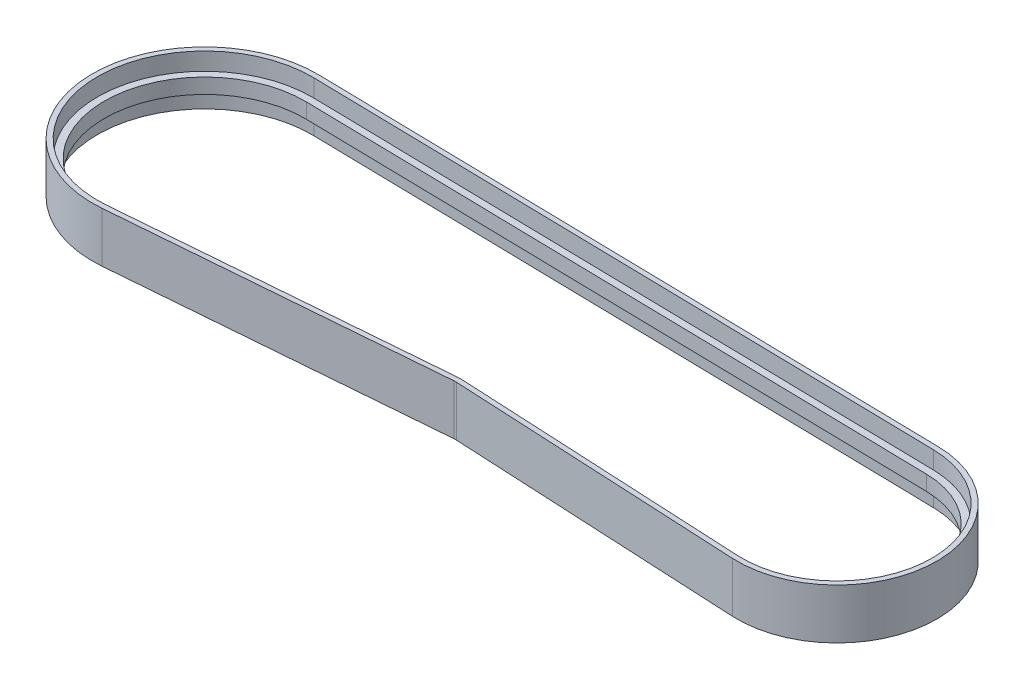
SolidWorks part; units mm, degrees
other "Markup1"
sketch "Sketch2" plane through (-23.4, 0, -23.4) normal (-0.231, -0.9167, -0.326) x (-0.972, 0.232, 0.0366)
sketch "Sketch3" plane through (-22.35, 0, -22.35) normal (-0.231, -0.9167, -0.326) x (-0.972, 0.232, 0.0366)
sketch "Sketch4" plane through (-22.35, 0, -22.35) normal (-0.231, -0.9167, -0.326) x (-0.972, 0.232, 0.0366)
sketch "Sketch5" plane through (-22.35, 0, -22.35) normal (-0.231, -0.9167, -0.326) x (-0.972, 0.232, 0.0366)
sketch "Sketch6" plane through (-22.35, 0, -22.35) normal (-0.231, -0.9167, -0.326) x (-0.972, 0.232, 0.0366)
sketch "Sketch9" plane through (-22.35, -5, -22.35) normal (-0.231, -0.9167, -0.326) x (-0.972, 0.232, 0.0366)
material "BUTYL"
ref_plane "Front Plane" through (0, 0, 0) normal (0, 0, 1) x (1, 0, 0)
ref_plane "Top Plane" through (0, 0, 0) normal (0, 1, 0) x (1, 0, 0)
ref_plane "Right Plane" through (0, 0, 0) normal (1, 0, 0) x (0, 0, -1)
sketch "Sketch1" plane through (0, 0, 0) normal (0, 1, 0) x (1, 0, 0)
  line L0 (0, 0) -> (126, 0) construction
  line L1 (0.4151, 21.346) -> (126.3675, 18.8964)
  line L2 (0.4346, 22.3458) -> (126.3869, 19.8962)
  line L5 (0.423, -21.3458) -> (125.0528, -18.8763) construction
  line L6 (0.4428, -22.3456) -> (125.0381, -19.8767) construction
  line L7 (125.0528, -18.8763) -> (67.15, -15.9709)
  line L8 (125.0381, -19.8767) -> (67.1167, -16.9704)
  line L9 (1.7388, -21.2791) -> (66.5748, -15.981)
  line L10 (1.8203, -22.2758) -> (66.6563, -16.9776)
  line L11 (0, 0) -> (66.9413, -20.466) construction
  arc A0 (0.4151, 21.346) -> (1.7388, -21.2791) centre (0, 0) ccw
  arc A1 (125.0528, -18.8763) -> (126.3675, 18.8964) centre (126, 0) ccw
  arc A2 (125.0381, -19.8767) -> (126.3869, 19.8962) centre (126, 0) ccw
  arc A3 (0.4346, 22.3458) -> (1.8203, -22.2758) centre (0, 0) ccw
  circle A4 centre (0, 0) radius 70 construction
  circle A5 centre (66.9413, -20.466) radius 1.25 construction
  arc A6 (67.1167, -16.9704) -> (66.6563, -16.9776) centre (66.9413, -20.466) ccw
  arc A8 (67.15, -15.9709) -> (66.5748, -15.981) centre (66.9413, -20.466) ccw
  arc A9 (0.4346, 22.3458) -> (0.4428, -22.3456) centre (0, 0) ccw construction
  arc A10 (0.4151, 21.346) -> (0.423, -21.3458) centre (0, 0) ccw construction
  point P17 (0, 0)
  point P22 (67.1167, -15.981)
  dimension "D1" = 42.7
  dimension "D3" = 37.8
  dimension "D5" = 140
  dimension "D6" = 7
  dimension "D7" = 2.5
  dimension "D9" = 1
  dimension "D2" = 126
  dimension "D8" = 17
  dimension "D4" = 1
extrude "Boss-Extrude1" add sketch "Sketch1" along normal mid plane 10
sketch "Sketch8" plane through (0, 0, 0) normal (0, 1, 0) x (1, 0, 0)
  line L15 (67.2177, -14.5725) -> (125.123, -17.478)
  line L16 (126.3403, 17.4967) -> (0.3879, 19.9462)
  line L17 (1.6248, -19.8837) -> (66.4608, -14.5856)
  line L18 (67.2177, -14.5725) -> (125.123, -17.478)
  line L19 (126.3403, 17.4967) -> (0.3879, 19.9462)
  line L20 (1.6248, -19.8837) -> (66.4608, -14.5856)
  line L32 (67.1404, -16.1706) -> (125.0428, -19.076)
  line L33 (126.3714, 19.0964) -> (0.419, 21.5459)
  line L34 (1.7551, -21.4784) -> (66.5911, -16.1803)
  line L35 (67.1404, -16.1706) -> (125.0428, -19.076)
  line L36 (126.3714, 19.0964) -> (0.419, 21.5459)
  line L37 (1.7551, -21.4784) -> (66.5911, -16.1803)
  arc A12 (67.2177, -14.5725) -> (66.4608, -14.5856) centre (66.9413, -20.466) ccw
  arc A13 (125.123, -17.478) -> (126.3403, 17.4967) centre (126, 0) ccw
  arc A14 (0.3879, 19.9462) -> (1.6248, -19.8837) centre (0, 0) ccw
  arc A15 (67.2177, -14.5725) -> (66.4608, -14.5856) centre (66.9413, -20.466) ccw
  arc A16 (125.123, -17.478) -> (126.3403, 17.4967) centre (126, 0) ccw
  arc A17 (0.3879, 19.9462) -> (1.6248, -19.8837) centre (0, 0) ccw
  arc A28 (67.1404, -16.1706) -> (66.5911, -16.1803) centre (66.9413, -20.466) ccw
  arc A29 (125.0428, -19.076) -> (126.3714, 19.0964) centre (126, 0) ccw
  arc A30 (0.419, 21.5459) -> (1.7551, -21.4784) centre (0, 0) ccw
  arc A31 (67.1404, -16.1706) -> (66.5911, -16.1803) centre (66.9413, -20.466) ccw
  arc A32 (125.0428, -19.076) -> (126.3714, 19.0964) centre (126, 0) ccw
  arc A33 (0.419, 21.5459) -> (1.7551, -21.4784) centre (0, 0) ccw
  dimension "D1" = 1.4
  dimension "D2" = 0.2
extrude "Boss-Extrude2" add sketch "Sketch8" along normal mid plane 3
